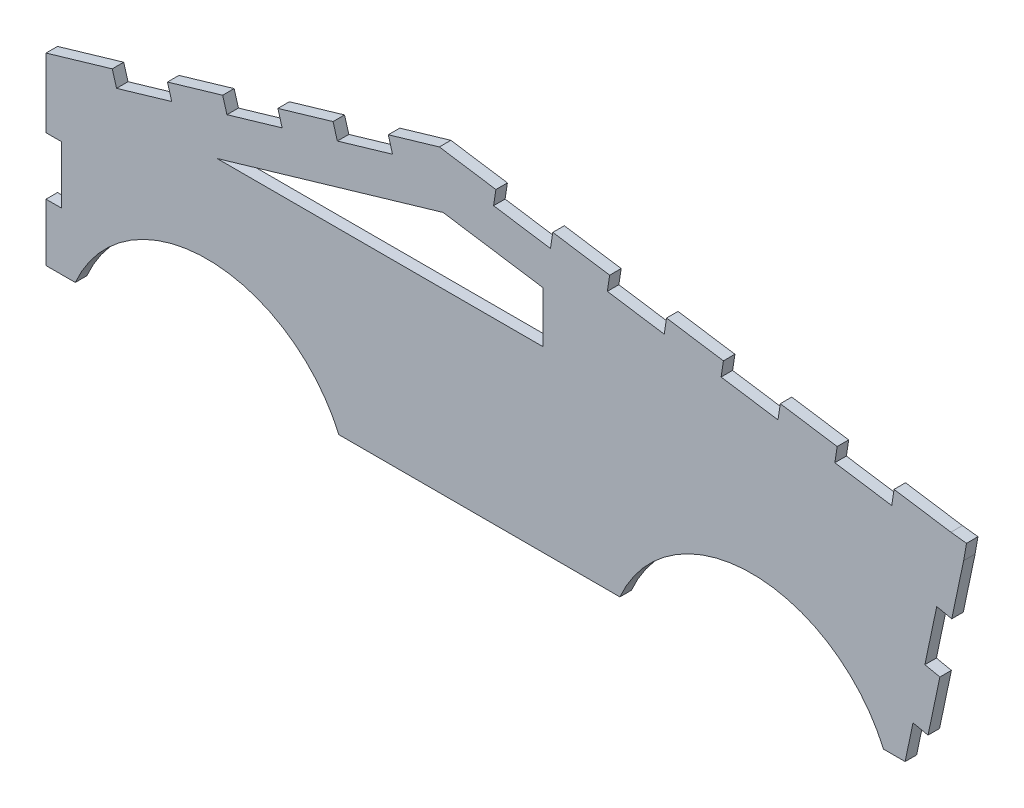
SolidWorks part; units mm, degrees
ref_plane "Front Plane" through (0, 0, 0) normal (0, 0, 1) x (1, 0, 0)
ref_plane "Top Plane" through (0, 0, 0) normal (0, 1, 0) x (1, 0, 0)
ref_plane "Right Plane" through (0, 0, 0) normal (1, 0, 0) x (0, 0, -1)
sketch "Sketch1" plane through (0, 0, 0) normal (0, 0, 1) x (1, 0, 0)
  line L0 (0, 0) -> (-220, 0)
  line L1 (-220, 0) -> (-220, 45)
  line L2 (-220, 45) -> (-121.163, 73.9869)
  line L3 (-121.163, 73.9869) -> (11.337, 53.8189)
  line L4 (11.337, 53.8189) -> (0, 0)
  line L5 (-179.4092, 46.4833) -> (-120.476, 63.7672)
  line L6 (-120.476, 63.7672) -> (-94.4092, 59.7995)
  line L7 (-179.4092, 46.4833) -> (-94.4092, 46.4833)
  line L8 (-94.4092, 46.4833) -> (-94.4092, 59.7995)
  line L9 (-217.1857, 35.4042) -> (-120.476, 63.7672) construction
  line L10 (9.2725, 44.018) -> (9.8322, 43.9327)
  line L11 (-120.476, 63.7672) -> (9.8322, 43.9327) construction
  dimension "D1" = 220
  dimension "D2" = 45
  dimension "D3" = 155
  dimension "D4" = 103
  dimension "D5" = 132.5
  dimension "D6" = 55
  dimension "D8" = 85
  dimension "D7" = 10
extrude "Boss-Extrude1" add sketch "Sketch1" against normal blind 3 contours L4 L3 L2 L1 L0 L8 L7 L5 L6
sketch "Sketch2" plane through (0, 0, 0) normal (0, 0, 1) x (1, 0, 0)
  line L0 (0, 0) -> (-220, 0) construction
  line L1 (-220, 0) -> (-220, 45) construction
  circle A0 centre (-182, -15) radius 37.5
  circle A1 centre (-40, -15) radius 37.5
  dimension "D3" = 75
  dimension "D5" = 75
  dimension "D1" = 15
  dimension "D2" = 38
  dimension "D4" = 40
  dimension "D6" = 15
extrude "Cut-Extrude1" cut sketch "Sketch2" against normal blind 3
sketch "Sketch3" plane through (0, 0, 0) normal (0, 0, 1) x (1, 0, 0)
  line L0 (-206.732, 53.0597) -> (-205.6063, 49.2214)
  line L1 (-220, 45) -> (-121.163, 73.9869) construction
  line L2 (-192.3382, 57.2811) -> (-191.2125, 53.4428)
  line L5 (-121.4377, 78.0748) -> (11.9389, 57.7733)
  line L6 (-221.1257, 48.8383) -> (-121.4377, 78.0748)
  line L7 (-121.4377, 78.0748) -> (-106.6946, 75.8307)
  line L8 (-221.1257, 48.8383) -> (-206.732, 53.0597)
  line L9 (-77.0363, 71.3164) -> (-77.6382, 67.3619)
  line L10 (-121.163, 73.9869) -> (11.337, 53.8189) construction
  line L11 (-3.4922, 56.0761) -> (-2.8903, 60.0305)
  line L12 (-18.3214, 58.3332) -> (-17.7195, 62.2877)
  line L13 (-177.9445, 61.5025) -> (-176.8188, 57.6642)
  line L14 (-163.5507, 65.7239) -> (-162.425, 61.8856)
  line L15 (-149.157, 69.9453) -> (-148.0313, 66.107)
  line L16 (-133.6375, 70.3284) -> (-134.7632, 74.1667)
  line L17 (-220, 45) -> (-205.6063, 49.2214)
  line L18 (-192.3382, 57.2811) -> (-177.9445, 61.5025)
  line L19 (-191.2125, 53.4428) -> (-176.8188, 57.6642)
  line L20 (-163.5507, 65.7239) -> (-149.157, 69.9453)
  line L21 (-162.425, 61.8856) -> (-148.0313, 66.107)
  line L22 (-134.7632, 74.1667) -> (-121.4377, 78.0748)
  line L23 (-133.6375, 70.3284) -> (-121.163, 73.9869)
  line L24 (-33.1506, 60.5904) -> (-32.5487, 64.5449)
  line L25 (-47.9798, 62.8476) -> (-47.3779, 66.802)
  line L26 (-62.809, 65.1048) -> (-62.2071, 69.0592)
  line L27 (-92.4674, 69.6191) -> (-91.8655, 73.5736)
  line L28 (-107.2966, 71.8763) -> (-106.6946, 75.8307)
  line L29 (11.337, 53.8189) -> (-3.4922, 56.0761)
  line L30 (-2.8903, 60.0305) -> (11.9389, 57.7733)
  line L31 (-18.3214, 58.3332) -> (-33.1506, 60.5904)
  line L32 (-32.5487, 64.5449) -> (-17.7195, 62.2877)
  line L33 (-47.9798, 62.8476) -> (-62.809, 65.1048)
  line L34 (-62.2071, 69.0592) -> (-47.3779, 66.802)
  line L35 (-77.6382, 67.3619) -> (-92.4674, 69.6191)
  line L36 (-91.8655, 73.5736) -> (-77.0363, 71.3164)
  line L37 (-107.2966, 71.8763) -> (-121.163, 73.9869)
  line L39 (-221.1257, 48.8383) -> (-224, 47.9954)
  line L45 (-224, 47.9954) -> (-224, 45)
  line L46 (-224, 0) -> (-220, 0)
  line L49 (-220, 30) -> (-224, 30)
  line L50 (-224, 0) -> (-224, 45)
  line L51 (-224, 0) -> (-224, 15)
  line L52 (11.9389, 57.7733) -> (16.0031, 57.298)
  line L55 (16.0031, 57.298) -> (15.2511, 52.9944)
  line L56 (-220, 0) -> (-220, 45) construction
  line L57 (-220, 15) -> (-224, 15)
  line L58 (-220, 45) -> (-220, 30)
  line L59 (-224, 30) -> (-224, 45)
  line L60 (-220, 15) -> (-220, 0)
  line L61 (8.2451, 39.141) -> (12.1592, 38.3165)
  line L62 (15.2511, 52.9944) -> (3.9141, -0.8245)
  line L63 (15.2511, 52.9944) -> (12.1592, 38.3165)
  line L64 (11.337, 53.8189) -> (0, 0) construction
  line L65 (5.1532, 24.4631) -> (9.0673, 23.6386)
  line L66 (2.0613, 9.7853) -> (5.9754, 8.9607)
  line L67 (11.337, 53.8189) -> (8.2451, 39.141)
  line L68 (9.0673, 23.6386) -> (5.9754, 8.9607)
  line L69 (5.1532, 24.4631) -> (2.0613, 9.7853)
  dimension "D3" = 15
  dimension "D4" = 15
  dimension "D5" = 15
  dimension "D6" = 15
  dimension "D7" = 15
  dimension "D8" = 4
  dimension "D9" = 15
  dimension "D10" = 15
  dimension "D11" = 15
  dimension "D12" = 15
  dimension "D13" = 15
  dimension "D14" = 15
  dimension "D15" = 15
  dimension "D18" = 86.76
  dimension "D19" = 15
  dimension "D20" = 15
  dimension "D21" = 15
  dimension "D22" = 15
  dimension "D1" = 4
  dimension "D16" = 4
extrude "Boss-Extrude4" add sketch "Sketch3" against normal blind 3
